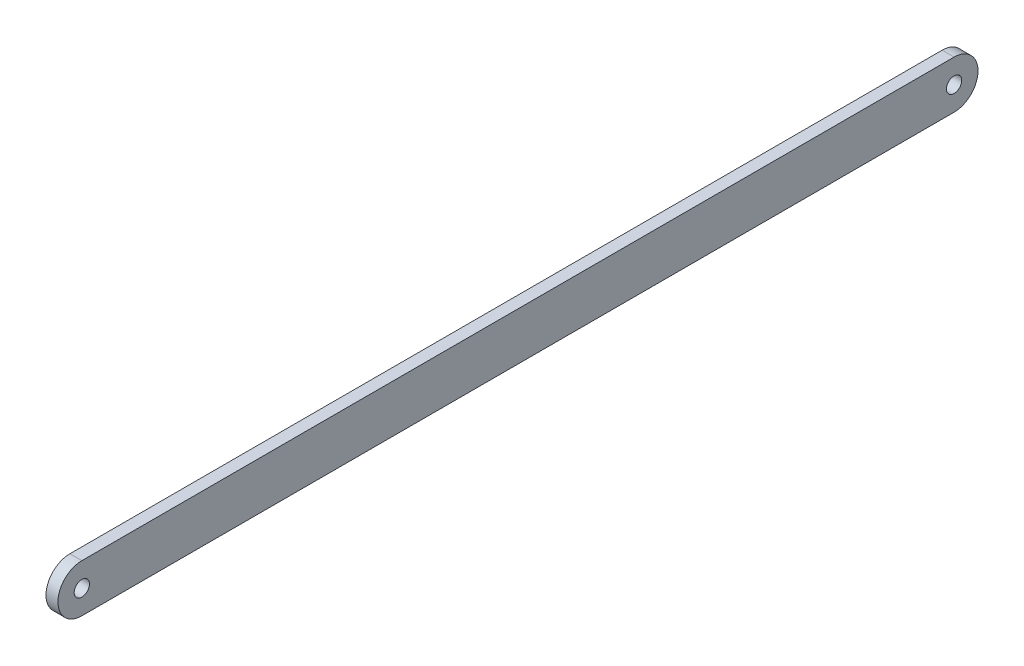
SolidWorks part; units mm, degrees
ref_plane "Front Plane" through (0, 0, 0) normal (0, 0, 1) x (1, 0, 0)
ref_plane "Top Plane" through (0, 0, 0) normal (0, 1, 0) x (1, 0, 0)
ref_plane "Right Plane" through (0, 0, 0) normal (1, 0, 0) x (0, 0, -1)
sketch "Sketch1" plane through (0, 0, 0) normal (1, 0, 0) x (0, 0, -1)
  line L0 (0, 0) -> (-231.775, 0) construction
  line L1 (0, -6.35) -> (-231.775, -6.35)
  line L2 (0, 6.35) -> (-231.775, 6.35)
  arc A0 (0, -6.35) -> (0, 6.35) centre (0, 0) ccw
  arc A1 (-231.775, 6.35) -> (-231.775, -6.35) centre (-231.775, 0) ccw
  circle A2 centre (-231.775, 0) radius 2.032
  circle A3 centre (0, 0) radius 2.032
  point P3 (-115.8875, 0)
  dimension "D3" = 4.064
  dimension "D1" = 231.775
  dimension "D2" = 12.7
extrude "Boss-Extrude1" add sketch "Sketch1" along normal blind 3.175
